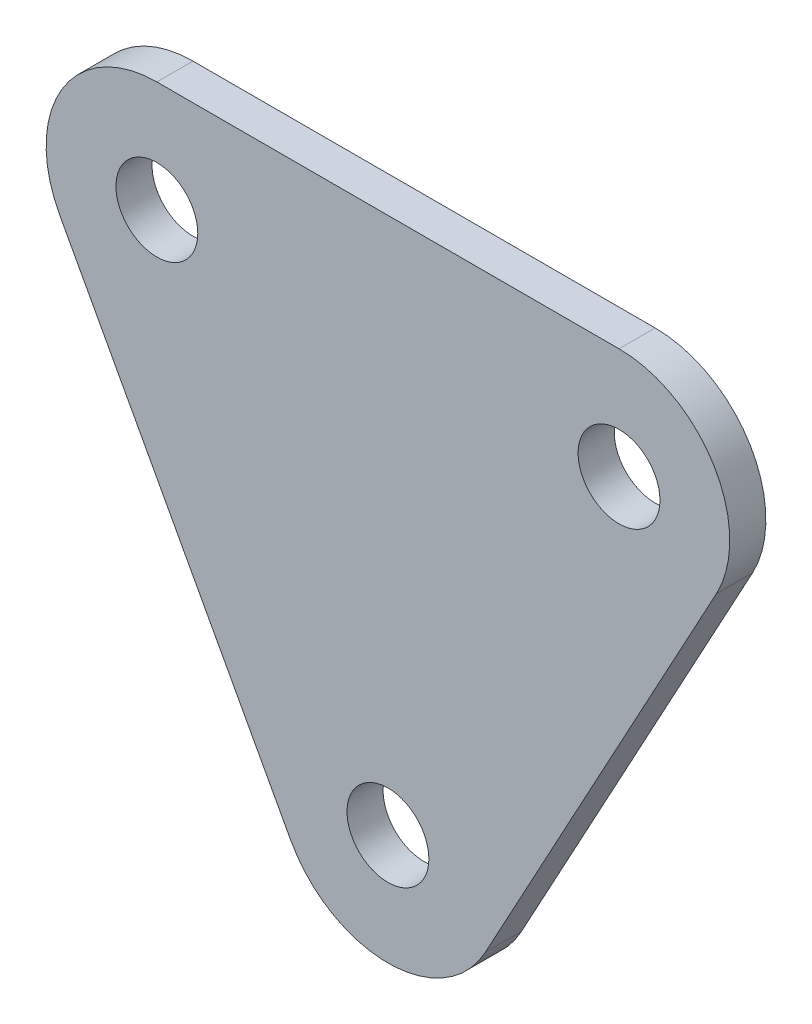
SolidWorks part; units mm, degrees
ref_plane "Ön Düzlem" through (0, 0, 0) normal (0, 0, 1) x (1, 0, 0)
ref_plane "Üst Düzlem" through (0, 0, 0) normal (0, 1, 0) x (1, 0, 0)
ref_plane "Sağ Düzlem" through (0, 0, 0) normal (1, 0, 0) x (0, 0, -1)
sketch "Çizim2" plane through (0, 0, 0) normal (0, 0, 1) x (1, 0, 0)
  line L0 (38.6397, 0) -> (134.6397, 0)
  line L1 (154.8575, -33.9655) -> (106.8575, -122.4655)
  line L2 (66.422, -122.4655) -> (18.422, -33.9655)
  arc A3 (106.8575, -122.4655) -> (66.422, -122.4655) centre (86.6397, -111.5) cw
  arc A4 (134.6397, 0) -> (154.8575, -33.9655) centre (134.6397, -23) cw
  arc A5 (38.6397, 0) -> (18.422, -33.9655) centre (38.6397, -23) ccw
  circle A6 centre (86.6397, -111.5) radius 8.5
  circle A7 centre (38.6397, -23) radius 8.5
  circle A8 centre (134.6397, -23) radius 8.5
  point P6 (0, 0)
  point P11 (86.6397, 0)
  point P18 (0, 0)
  dimension "D1" = 96
  dimension "D2" = 14.5
  dimension "D3" = 88.5
  dimension "D4" = 23
extrude "Yükseklik-Ekstrüzyon1" add sketch "Çizim2" along normal blind 7.5
